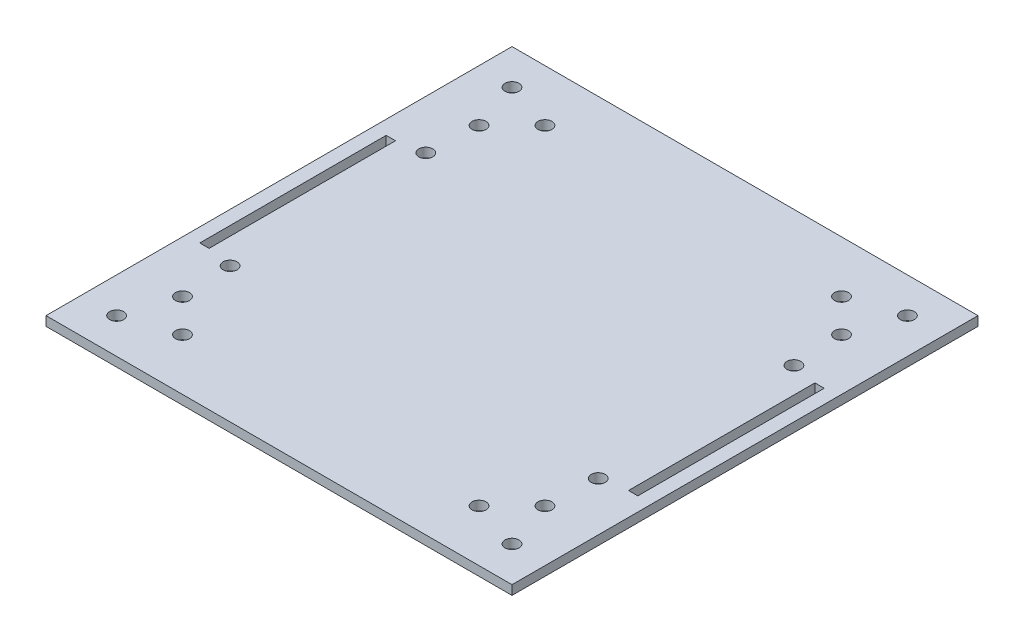
SolidWorks part; units mm, degrees
material "Thornel Mat VMA"
ref_plane "前视基准面" through (0, 0, 0) normal (0, 0, 1) x (1, 0, 0)
ref_plane "上视基准面" through (0, 0, 0) normal (0, 1, 0) x (1, 0, 0)
ref_plane "右视基准面" through (0, 0, 0) normal (1, 0, 0) x (0, 0, -1)
other "Configuration Table"
sketch "草图1" plane through (0, 0, 0) normal (0, 1, 0) x (1, 0, 0)
  line L1 (-50, -50) -> (50, -50)
  line L2 (-50, -50) -> (-50, 50)
  line L3 (-50, 50) -> (50, 50)
  line L4 (50, -50) -> (50, 50)
  line L5 (-50, -50) -> (50, 50) construction
  line L6 (-50, 50) -> (50, -50) construction
  point P0 (0, 0)
  dimension "D1" = 100
  dimension "D2" = 100
extrude "凸台-拉伸1" add sketch "草图1" along normal blind 2
sketch "草图3" plane through (0, 2, 0) normal (0, 1, 0) x (1, 0, 0)
  line L0 (-1000, 0) -> (49000, 0) construction
  line L1 (-42.4264, 42.4264) -> (0, 0) construction
  line L2 (-42.9749, 27.7358) -> (35312.3642, 35383.0749) construction
  line L3 (0, -1000) -> (0, 49000) construction
  circle A0 centre (0, 0) radius 60 construction
  circle A1 centre (-42.4264, 42.4264) radius 1.5
  circle A2 centre (-31.8198, 38.8909) radius 1.5
  circle A3 centre (-38.8909, 31.8198) radius 1.5
  circle A4 centre (-31.8198, -38.8909) radius 1.5
  circle A5 centre (-38.8909, -31.8198) radius 1.5
  circle A6 centre (-42.4264, -42.4264) radius 1.5
  circle A7 centre (31.8198, 38.8909) radius 1.5
  circle A8 centre (38.8909, 31.8198) radius 1.5
  circle A9 centre (42.4264, 42.4264) radius 1.5
  circle A10 centre (31.8198, -38.8909) radius 1.5
  circle A11 centre (42.4264, -42.4264) radius 1.5
  circle A12 centre (38.8909, -31.8198) radius 1.5
  dimension "D1" = 120
  dimension "D3" = 3
  dimension "D6" = 3
  dimension "D7" = 3
  dimension "D8" = 5
  dimension "D9" = 5
  dimension "D2" = 45
  dimension "D4" = 90
  dimension "D5" = 10
extrude "切除-拉伸2" cut sketch "草图3" against normal through all
sketch "草图4" plane through (0, 0, 0) normal (0, -1, 0) x (1, 0, 0)
  line L0 (0, -1000) -> (0, 49000) construction
  line L1 (-1000, 0) -> (49000, 0) construction
  circle A0 centre (-39.5, 21) radius 1.5
  circle A1 centre (39.5, 21) radius 1.5
  circle A2 centre (39.5, -21) radius 1.5
  circle A3 centre (-39.5, -21) radius 1.5
  dimension "D1" = 21
  dimension "D2" = 39.5
  dimension "D3" = 3
extrude "切除-拉伸3" cut sketch "草图4" against normal through all
sketch "草图5" plane through (0, 0, 0) normal (0, -1, 0) x (1, 0, 0)
  line L0 (-50, -50) -> (-50, 50) construction
  line L1 (-47, -20) -> (-45, -20)
  line L2 (-47, -20) -> (-47, 20)
  line L3 (-47, 20) -> (-45, 20)
  line L4 (-45, -20) -> (-45, 20)
  line L5 (-47, -20) -> (-45, 20) construction
  line L6 (-47, 20) -> (-45, -20) construction
  line L7 (0, -1000) -> (0, 49000) construction
  line L8 (47, 20) -> (45, 20)
  line L9 (45, -20) -> (45, 20)
  line L10 (47, -20) -> (45, -20)
  line L11 (47, -20) -> (47, 20)
  point P0 (-46, 0)
  dimension "D1" = 40
  dimension "D2" = 2
  dimension "D3" = 3
  dimension "D4" = 0
extrude "切除-拉伸4" cut sketch "草图5" against normal through all
